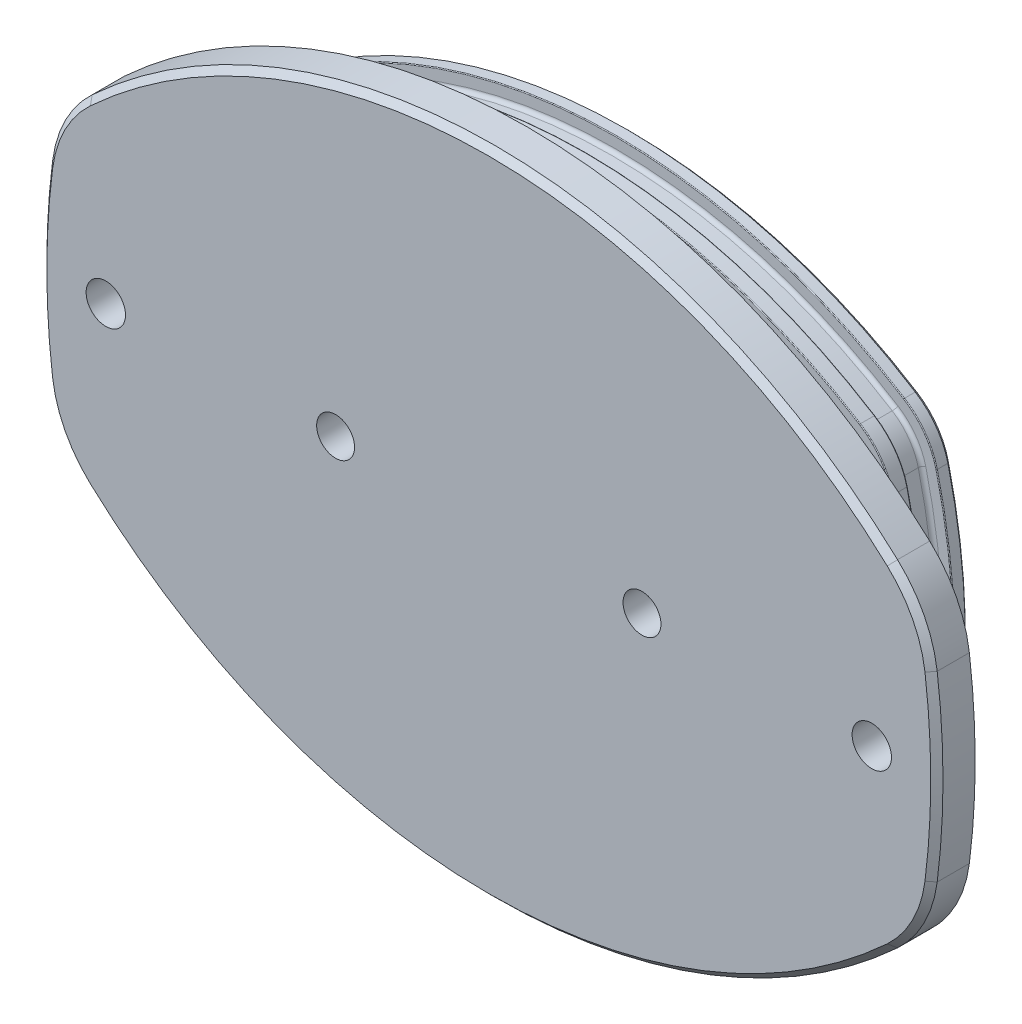
SolidWorks part; units mm, degrees
material "6061-T6 (SS)"
ref_plane "Front Plane" through (0, 0, 0) normal (0, 0, 1) x (1, 0, 0)
ref_plane "Top Plane" through (0, 0, 0) normal (0, 1, 0) x (1, 0, 0)
ref_plane "Right Plane" through (0, 0, 0) normal (1, 0, 0) x (0, 0, -1)
sketch "Sketch1" plane through (0, 0, 0) normal (0, 0, 1) x (1, 0, 0)
  line L0 (45.085, 0) -> (-45.085, 0) construction
  line L1 (0, -32.5333) -> (0, 49967.4667) construction
  arc A0 (48.038, 31.8585) -> (-48.038, 31.8585) centre (0, -44.45) ccw construction
  arc A1 (-53.6088, 24.1266) -> (-53.6088, -24.1266) centre (45.085, 0) ccw construction
  arc A2 (-48.038, -31.8585) -> (48.038, -31.8585) centre (0, 44.45) ccw construction
  arc A3 (-48.038, -31.8585) -> (-53.6088, -24.1266) centre (-41.2721, -21.1108) cw construction
  arc A4 (48.038, -31.8585) -> (53.6088, -24.1266) centre (41.2721, -21.1108) ccw construction
  arc A5 (53.6088, -24.1266) -> (53.6088, 24.1266) centre (-45.085, 0) ccw construction
  arc A6 (48.038, 31.8585) -> (53.6088, 24.1266) centre (41.2721, 21.1108) cw construction
  arc A7 (-48.038, 31.8585) -> (-53.6088, 24.1266) centre (-41.2721, 21.1108) ccw construction
  arc A8 (-61.6277, 26.0869) -> (-61.6277, -26.0869) centre (45.085, 0) ccw
  arc A9 (-52.4358, -38.8444) -> (-61.6277, -26.0869) centre (-41.2721, -21.1108) cw
  arc A10 (-52.4358, -38.8444) -> (52.4358, -38.8444) centre (0, 44.45) ccw
  arc A11 (52.4358, -38.8444) -> (61.6277, -26.0869) centre (41.2721, -21.1108) ccw
  arc A12 (61.6277, -26.0869) -> (61.6277, 26.0869) centre (-45.085, 0) ccw
  arc A13 (52.4358, 38.8444) -> (61.6277, 26.0869) centre (41.2721, 21.1108) cw
  arc A14 (52.4358, 38.8444) -> (-52.4358, 38.8444) centre (0, -44.45) ccw
  arc A15 (-52.4358, 38.8444) -> (-61.6277, 26.0869) centre (-41.2721, 21.1108) ccw
  dimension "D3" = 12.7
  dimension "D4" = 101.6
  dimension "D6" = 90.17
  dimension "D1" = 44.45
  dimension "D2" = 90.17
  dimension "D5" = 8.255
extrude "Boss-Extrude1" add sketch "Sketch1" along normal blind 6.35
sketch "Sketch2" plane through (0, 0, 0) normal (0, 0, -1) x (-1, 0, 0)
  arc A0 (-46.0444, 20.2167) -> (-46.0444, -20.2167) centre (45.085, 0) ccw
  arc A1 (41.9143, -25.9294) -> (46.0444, -20.2167) centre (37.3654, -18.2913) ccw
  arc A2 (-41.9143, -25.9294) -> (41.9143, -25.9294) centre (0, 44.45) ccw
  arc A3 (-43.6401, -24.8725) -> (43.6401, -24.8725) centre (0, 44.45) ccw construction
  arc A4 (46.0444, -20.2167) -> (46.0444, 20.2167) centre (-45.085, 0) ccw
  arc A5 (45.5899, -22.1663) -> (45.5899, 22.1663) centre (-45.085, 0) ccw construction
  arc A6 (41.9143, 25.9294) -> (-41.9143, 25.9294) centre (0, -44.45) ccw
  arc A7 (-41.9143, -25.9294) -> (-46.0444, -20.2167) centre (-37.3654, -18.2913) cw
  arc A8 (-41.9143, 25.9294) -> (-46.0444, 20.2167) centre (-37.3654, 18.2913) ccw
  arc A9 (46.0444, 20.2167) -> (41.9143, 25.9294) centre (37.3654, 18.2913) ccw
  arc A10 (-45.5899, 22.1663) -> (-45.5899, -22.1663) centre (45.085, 0) ccw construction
  arc A11 (43.6401, 24.8725) -> (-43.6401, 24.8725) centre (0, -44.45) ccw construction
  arc A25 (53.6088, 24.1266) -> (48.038, 31.8585) centre (41.2721, 21.1108) ccw
  arc A26 (48.038, 31.8585) -> (-48.038, 31.8585) centre (0, -44.45) ccw
  arc A27 (-48.038, 31.8585) -> (-53.6088, 24.1266) centre (-41.2721, 21.1108) ccw
  arc A28 (-53.6088, 24.1266) -> (-53.6088, -24.1266) centre (45.085, 0) ccw
  arc A29 (-53.6088, -24.1266) -> (-48.038, -31.8585) centre (-41.2721, -21.1108) ccw
  arc A30 (-48.038, -31.8585) -> (48.038, -31.8585) centre (0, 44.45) ccw
  arc A31 (48.038, -31.8585) -> (53.6088, -24.1266) centre (41.2721, -21.1108) ccw
  arc A32 (53.6088, -24.1266) -> (53.6088, 24.1266) centre (-45.085, 0) ccw
  arc A33 (53.6088, 24.1266) -> (48.038, 31.8585) centre (41.2721, 21.1108) ccw
  arc A34 (48.038, 31.8585) -> (-48.038, 31.8585) centre (0, -44.45) ccw
  arc A35 (-48.038, 31.8585) -> (-53.6088, 24.1266) centre (-41.2721, 21.1108) ccw
  arc A36 (-53.6088, 24.1266) -> (-53.6088, -24.1266) centre (45.085, 0) ccw
  arc A37 (-53.6088, -24.1266) -> (-48.038, -31.8585) centre (-41.2721, -21.1108) ccw
  arc A38 (-48.038, -31.8585) -> (48.038, -31.8585) centre (0, 44.45) ccw
  arc A39 (48.038, -31.8585) -> (53.6088, -24.1266) centre (41.2721, -21.1108) ccw
  arc A40 (53.6088, -24.1266) -> (53.6088, 24.1266) centre (-45.085, 0) ccw
  arc A41 (-45.5899, -22.1663) -> (-43.6401, -24.8725) centre (-41.2721, -21.1108) ccw construction
  arc A42 (-43.6401, 24.8725) -> (-45.5899, 22.1663) centre (-41.2721, 21.1108) ccw construction
  arc A43 (45.5899, 22.1663) -> (43.6401, 24.8725) centre (41.2721, 21.1108) ccw construction
  arc A44 (43.6401, -24.8725) -> (45.5899, -22.1663) centre (41.2721, -21.1108) ccw construction
  dimension "D3" = 8.89
  dimension "D1" = 8.255
  dimension "D2" = 8.255
extrude "Boss-Extrude2" add sketch "Sketch2" along normal blind 17.145
sketch "Sketch10" plane through (0, 0, 6.35) normal (0, 0, 1) x (1, 0, 0)
  arc A0 (66.7595, 27.8733) -> (-66.7595, 27.8733) centre (0, -44.45) ccw
  arc A1 (-66.7595, -27.8733) -> (66.7595, -27.8733) centre (0, 44.45) ccw
  arc A2 (-52.4358, -38.8444) -> (52.4358, -38.8444) centre (0, 44.45) ccw construction
  arc A3 (52.4358, 38.8444) -> (-52.4358, 38.8444) centre (0, -44.45) ccw construction
  arc A20 (-70.8802, 28.3488) -> (-70.8802, -28.3488) centre (45.085, 0) ccw
  arc A21 (-73.3322, 15.1315) -> (-73.3322, -15.1315) centre (45.085, 0) ccw
  arc A22 (66.7595, 27.8733) -> (73.3322, 15.1315) centre (52.5462, 12.4754) cw
  arc A23 (70.8802, -28.3488) -> (70.8802, 28.3488) centre (-45.085, 0) ccw
  arc A24 (73.3322, -15.1315) -> (73.3322, 15.1315) centre (-45.085, 0) ccw
  arc A25 (66.7595, -27.8733) -> (73.3322, -15.1315) centre (52.5462, -12.4754) ccw
  arc A26 (-66.7595, -27.8733) -> (-73.3322, -15.1315) centre (-52.5462, -12.4754) cw
  arc A27 (-66.7595, 27.8733) -> (-73.3322, 15.1315) centre (-52.5462, 12.4754) ccw
  dimension "D3" = 20.955
  dimension "D1" = 9.525
  dimension "D2" = 9.525
extrude "Boss-Extrude4" add sketch "Sketch10" against normal up to surface (6.35 mm away) up to face at (0, 0, 0)
chamfer "Chamfer1" distance 1.016 angle 45 8 edges at (0, 53.975, 6.35) (0, -53.975, 6.35) (71.1694, 22.082, 6.35) (74.295, 0, 6.35) (71.1694, -22.082, 6.35) (-71.1694, -22.082, 6.35) (-74.295, 0, 6.35) (-71.1694, 22.082, 6.35)
sketch "Sketch4" plane through (0, 0, -17.145) normal (0, 0, -1) x (-1, 0, 0)
  line L0 (0, 0) -> (-42.5874, 19.8588) construction
  line L1 (0, 0) -> (-48.26, 0) construction
  arc A2 (0, 37.465) -> (-45.1486, 23.8996) centre (0, -44.45) ccw construction
  arc A3 (-45.1486, 23.8996) -> (-48.26, 0) centre (45.085, 0) ccw construction
  arc A4 (-46.0444, 20.2167) -> (-46.0444, -20.2167) centre (45.085, 0) ccw construction
  arc A5 (41.9143, 25.9294) -> (-41.9143, 25.9294) centre (0, -44.45) ccw construction
  circle A8 centre (-42.5874, 19.8588) radius 4.7625
  arc A9 (-46.0444, 20.2167) -> (-46.0444, -20.2167) centre (45.085, 0) ccw construction
  point P13 (-48.26, 0)
  dimension "D1" = 9.525
  dimension "D2" = 46.99
  dimension "D3" = 25
extrude "Boss-Extrude3" [suppressed] add sketch "Sketch4" against normal up to surface (17.145 mm away)
mirror "Mirror1" [suppressed] about plane through (0, 0, 0) normal (1, 0, 0)
mirror "Mirror2" [suppressed] about plane through (0, 0, 0) normal (0, 1, 0)
fillet "Fillet1" [suppressed] radius 6.35
hole_wizard "#8-32 Tapped Hole1" [suppressed] positions "Sketch6" profile "Sketch7" tap size "#8-32" standard "ANSI Inch"
sketch "Sketch6" [suppressed] plane through (0, 0, -17.145) normal (0, 0, -1) x (-1, 0, 0)
  point P0 (-42.5874, 19.8588)
  point P4 (42.5874, 19.8588)
  point P7 (42.5874, -19.8588)
  point P10 (-42.5874, -19.8588)
sketch "Sketch7" plane through (42.5874, 19.8588, -17.145) normal (1, 0, 0) x (0, 1, 0)
  line L0 (0, 0) -> (0, 12.2138)
  line L1 (0, 12.2138) -> (1.7272, 11.176)
  line L2 (1.7272, 11.176) -> (1.7272, 0)
  line L5 (1.7272, 0) -> (0, 0)
  line L10 (0, 12.2138) -> (-1.7272, 11.176) construction
  line L11 (0, -6.35) -> (0, 107.95) construction
  dimension "Tap Drill Dia." = 3.4544
  dimension "Tap Drill Depth" = 11.176
  dimension "Drill Angle" = 118
sketch "Sketch8" plane through (0, 0, 0) normal (0, 1, 0) x (1, 0, 0)
  line L0 (-56.515, 0) -> (-56.1594, 0)
  line L1 (-53.6088, 17.145) -> (-56.515, 17.145) construction
  line L2 (-56.515, 17.145) -> (-56.515, 0)
  line L3 (-53.6088, 0) -> (-56.515, 0) construction
  line L4 (-56.515, 17.145) -> (-56.515, 0) construction
  line L5 (-56.1594, 17.145) -> (-56.515, 17.145)
  line L6 (-56.1594, 0) -> (-56.1594, 2.4977)
  line L7 (-56.1594, 2.4977) -> (-53.6702, 2.4977)
  line L8 (-53.6702, 2.4977) -> (-53.6702, 7.3237)
  line L9 (-53.6702, 7.3237) -> (-56.1594, 7.3237)
  line L10 (-56.1594, 7.3237) -> (-56.1594, 9.8213)
  line L11 (-56.1594, 9.8213) -> (-53.6702, 9.8213)
  line L12 (-53.6702, 9.8213) -> (-53.6702, 14.6473)
  line L13 (-53.6702, 14.6473) -> (-56.1594, 14.6473)
  line L14 (-56.1594, 14.6473) -> (-56.1594, 17.145)
  line L15 (66.7595, 0) -> (-66.7595, 0) construction
  point P0 (-56.515, 0)
  dimension "D1" = 4.826
  dimension "D2" = 2.8448
  dimension "D3" = 0.3556
sketch "Sketch9" plane through (0, 0, -17.145) normal (0, 0, -1) x (-1, 0, 0)
  arc A0 (53.6088, -24.1266) -> (53.6088, 24.1266) centre (-45.085, 0) ccw construction
  arc A1 (48.038, -31.8585) -> (53.6088, -24.1266) centre (41.2721, -21.1108) ccw construction
  arc A2 (-48.038, -31.8585) -> (48.038, -31.8585) centre (0, 44.45) ccw construction
  arc A3 (-53.6088, -24.1266) -> (-48.038, -31.8585) centre (-41.2721, -21.1108) ccw construction
  arc A4 (-53.6088, 24.1266) -> (-53.6088, -24.1266) centre (45.085, 0) ccw construction
  arc A5 (-48.038, 31.8585) -> (-53.6088, 24.1266) centre (-41.2721, 21.1108) ccw construction
  arc A6 (48.038, 31.8585) -> (-48.038, 31.8585) centre (0, -44.45) ccw construction
  arc A7 (53.6088, 24.1266) -> (48.038, 31.8585) centre (41.2721, 21.1108) ccw construction
  arc A8 (53.6088, -24.1266) -> (53.6088, 24.1266) centre (-45.085, 0) ccw
  arc A9 (48.038, -31.8585) -> (53.6088, -24.1266) centre (41.2721, -21.1108) ccw
  arc A10 (-48.038, -31.8585) -> (48.038, -31.8585) centre (0, 44.45) ccw
  arc A11 (-53.6088, -24.1266) -> (-48.038, -31.8585) centre (-41.2721, -21.1108) ccw
  arc A12 (-53.6088, 24.1266) -> (-53.6088, -24.1266) centre (45.085, 0) ccw
  arc A13 (-48.038, 31.8585) -> (-53.6088, 24.1266) centre (-41.2721, 21.1108) ccw
  arc A14 (48.038, 31.8585) -> (-48.038, 31.8585) centre (0, -44.45) ccw
  arc A15 (53.6088, 24.1266) -> (48.038, 31.8585) centre (41.2721, 21.1108) ccw
sweep "Cut-Sweep1" cut profiles "Sketch8" path "Sketch9"
fillet "Fillet2" radius 0.127 32 edges at (-51.2876, -28.327, -14.6473) (0, -45.3644, -14.6473) (51.2876, -28.327, -14.6473) (56.1594, 0, -14.6473) (51.2876, 28.327, -14.6473) (0, 45.3644, -14.6473) (-51.2876, 28.327, -14.6473) (-51.2876, -28.327, -9.8213) (0, -45.3644, -9.8213) (51.2876, -28.327, -9.8213) (56.1594, 0, -9.8213) (51.2876, 28.327, -9.8213) (0, 45.3644, -9.8213) (-51.2876, 28.327, -9.8213) (-51.2876, -28.327, -7.3237) (0, -45.3644, -7.3237) (51.2876, -28.327, -7.3237) (56.1594, 0, -7.3237) (51.2876, 28.327, -7.3237) (0, 45.3644, -7.3237) (-51.2876, 28.327, -7.3237) (-51.2876, -28.327, -2.4977) (0, -45.3644, -2.4977) (51.2876, -28.327, -2.4977) (56.1594, 0, -2.4977) (51.2876, 28.327, -2.4977) (0, 45.3644, -2.4977) (-51.2876, 28.327, -2.4977)
fillet "Fillet3" radius 0.635 32 edges at (-49.268, -26.8719, -14.6473) (0, -42.8752, -14.6473) (49.268, -26.8719, -14.6473) (53.6702, 0, -14.6473) (49.268, 26.8719, -14.6473) (0, 42.8752, -14.6473) (-49.268, 26.8719, -14.6473) (-49.268, -26.8719, -9.8213) (0, -42.8752, -9.8213) (49.268, -26.8719, -9.8213) (53.6702, 0, -9.8213) (49.268, 26.8719, -9.8213) (0, 42.8752, -9.8213) (-49.268, 26.8719, -9.8213) (-49.268, -26.8719, -7.3237) (0, -42.8752, -7.3237) (49.268, -26.8719, -7.3237) (53.6702, 0, -7.3237) (49.268, 26.8719, -7.3237) (0, 42.8752, -7.3237) (-49.268, 26.8719, -7.3237) (-49.268, -26.8719, -2.4977) (0, -42.8752, -2.4977) (49.268, -26.8719, -2.4977) (53.6702, 0, -2.4977) (49.268, 26.8719, -2.4977) (0, 42.8752, -2.4977) (-49.268, 26.8719, -2.4977)
chamfer "Chamfer2" distance 0.635 angle 45 8 edges at (56.1594, 0, -17.145) (51.2876, -28.327, -17.145) (51.2876, 28.327, -17.145) (0, -45.3644, -17.145) (0, 45.3644, -17.145) (-51.2876, -28.327, -17.145) (-51.2876, 28.327, -17.145)
sketch "Sketch13" plane through (0, 0, 6.35) normal (0, 0, 1) x (1, 0, 0)
  line L1 (0, 0) -> (0, -50000) construction
  arc A0 (-72.3244, 15.0027) -> (-72.3244, -15.0027) centre (45.085, 0) ccw construction
  point P5 (-63.5, 0)
  point P9 (63.5, 0)
  point P11 (-73.279, 0)
  dimension "D1" = 127
hole_wizard "1/4 Clearance Hole1" positions "Sketch15" profile "Sketch14" hole size "1/4" standard "ANSI Inch" end condition through all
sketch "Sketch15" plane through (0, 0, 6.35) normal (0, 0, 1) x (1, 0, 0)
  point P0 (-63.5, 0)
  point P3 (63.5, 0)
sketch "Sketch14" plane through (-63.5, 0, 6.35) normal (1, 0, 0) x (0, -1, 0)
  line L0 (0, 0) -> (0, 23.495)
  line L1 (0, 23.495) -> (3.2639, 23.495)
  line L2 (3.2639, 23.495) -> (3.2639, 0)
  line L5 (3.2639, 0) -> (0, 0)
  line L11 (0, -6.35) -> (0, 107.95) construction
  dimension "Thru Hole Dia." = 6.5278
  dimension "Thru Hole Depth" = 23.495
sketch "Sketch16" plane through (0, 0, 6.35) normal (0, 0, 1) x (1, 0, 0)
  line L1 (0, 0) -> (0, -50000) construction
  point P0 (-25.4, 0)
  point P1 (25.4, 0)
  dimension "D1" = 50.8
sketch "Sketch19" plane through (0, 0, 0) normal (0, 0, -1) x (-1, 0, 0)
  circle A0 centre (-25.4, 0) radius 7.9375
  circle A1 centre (25.4, 0) radius 7.9375
  dimension "D2" = 15.875
extrude "Boss-Extrude5" add sketch "Sketch19" along normal blind 14.2875
hole_wizard "Tapped Hole for #10-24 Helicoil2" positions "Sketch21" profile "Sketch20" tap size "#10-24" standard "Helicoil® Inch"
sketch "Sketch21" plane through (0, 0, 6.35) normal (0, 0, 1) x (1, 0, 0)
  point P0 (-25.4, 0)
  point P3 (25.4, 0)
sketch "Sketch20" plane through (-25.4, 0, 6.35) normal (1, 0, 0) x (0, -1, 0)
  line L0 (0, 0) -> (0, 15.7738)
  line L1 (0, 15.7738) -> (2.5794, 14.224)
  line L2 (2.5794, 14.224) -> (2.5794, 12.192)
  line L3 (2.5794, 12.192) -> (3.1432, 12.192)
  line L4 (3.1432, 12.192) -> (3.1432, 0)
  line L5 (3.1432, 0) -> (0, 0)
  line L10 (0, 15.7738) -> (-2.5794, 14.224) construction
  line L11 (0, -6.35) -> (0, 107.95) construction
  dimension "Tap Drill Dia." = 5.1587
  dimension "Tap Drill Depth" = 14.224
  dimension "Thread Major Dia." = 6.2865
  dimension "Thread Depth" = 12.192
  dimension "Drill Angle" = 118
